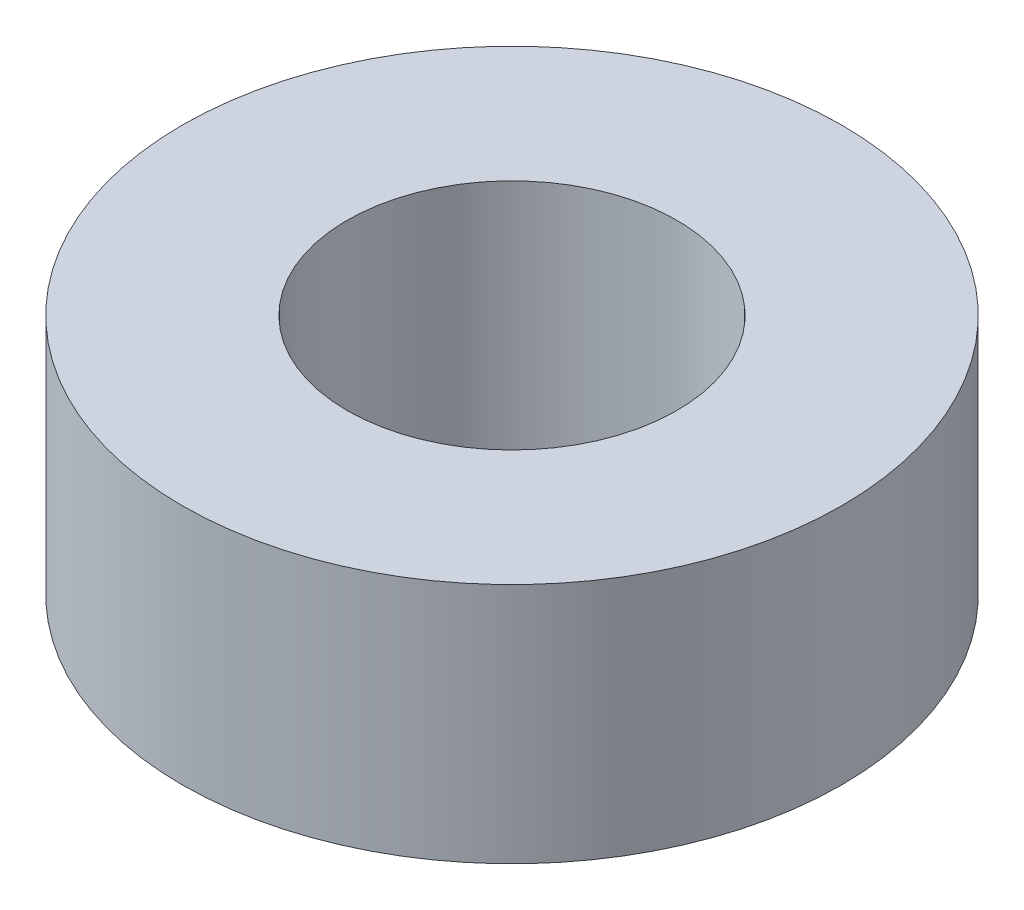
SolidWorks part; units mm, degrees
ref_plane "前视基准面" through (0, 0, 0) normal (0, 0, 1) x (1, 0, 0)
ref_plane "上视基准面" through (0, 0, 0) normal (0, 1, 0) x (1, 0, 0)
ref_plane "右视基准面" through (0, 0, 0) normal (1, 0, 0) x (0, 0, -1)
other "Configuration Table"
sketch "草图1" plane through (0, 0, 0) normal (0, 1, 0) x (1, 0, 0)
  circle A0 centre (0, 0) radius 3
  circle A1 centre (0, 0) radius 1.5
  dimension "D1" = 6
  dimension "D2" = 3
extrude "凸台-拉伸1" add sketch "草图1" along normal blind 2.2
